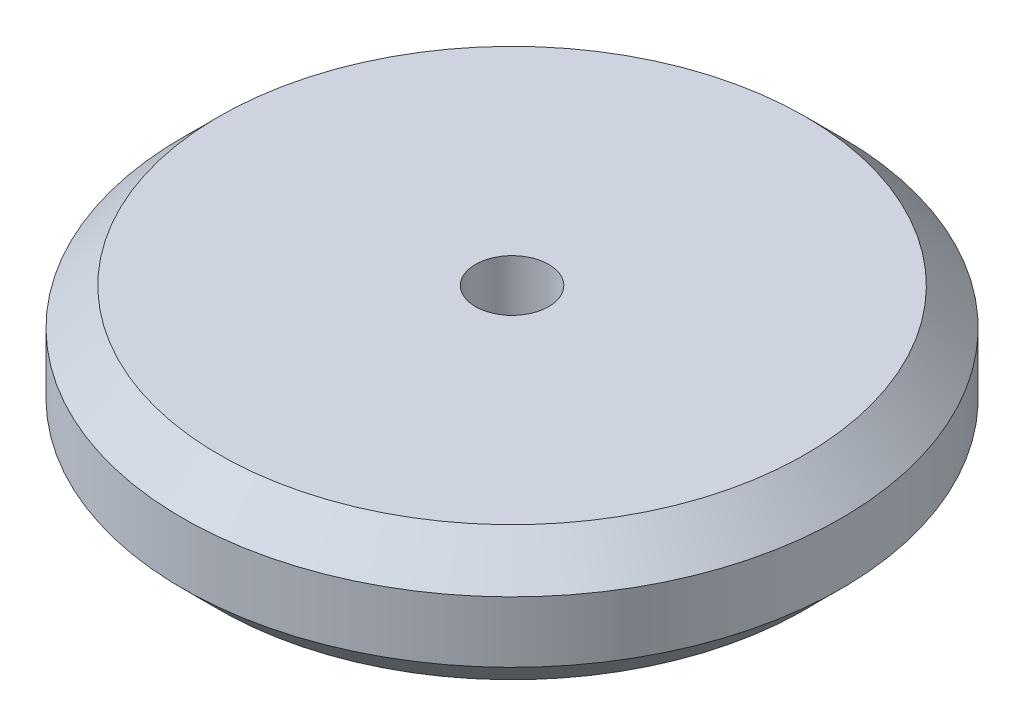
SolidWorks part; units mm, degrees
ref_plane "Front Plane" through (0, 0, 0) normal (0, 0, 1) x (1, 0, 0)
ref_plane "Top Plane" through (0, 0, 0) normal (0, 1, 0) x (1, 0, 0)
ref_plane "Right Plane" through (0, 0, 0) normal (1, 0, 0) x (0, 0, -1)
sketch "Sketch1" plane through (0, 0, 0) normal (0, 0, 1) x (1, 0, 0)
  line L0 (0, 0) -> (0, 28.5001) construction
  line L1 (0, 0) -> (10, 0) construction
  line L2 (10, 0) -> (10, 6)
  line L3 (10, 6) -> (24, 6)
  line L4 (24, 6) -> (27, 9)
  line L5 (27, 9) -> (27, 14)
  line L6 (27, 14) -> (24, 17)
  line L7 (24, 17) -> (0, 17) construction
  line L9 (24, 17) -> (3, 17)
  line L10 (3, 17) -> (3, 0)
  line L11 (3, 0) -> (10, 0)
  dimension "D1" = 3
  dimension "D2" = 27
  dimension "D3" = 10
  dimension "D4" = 3
  dimension "D5" = 3
  dimension "D6" = 3
  dimension "D7" = 3
  dimension "D8" = 6
  dimension "D9" = 11
revolve "Revolve1" add sketch "Sketch1" angle 360 about L0
sketch "Sketch2" plane through (0, 0, 0) normal (0, 0, 1) x (1, 0, 0)
  line L0 (0, 0) -> (0, 17) construction
  line L1 (3, 17) -> (-3, 17) construction
  line L2 (-10, 0) -> (10, 0) construction
  circle A0 centre (0, 3) radius 1.65
  dimension "D1" = 3.3
  dimension "D2" = 3
extrude "Cut-Extrude1" cut sketch "Sketch2" against normal through all
